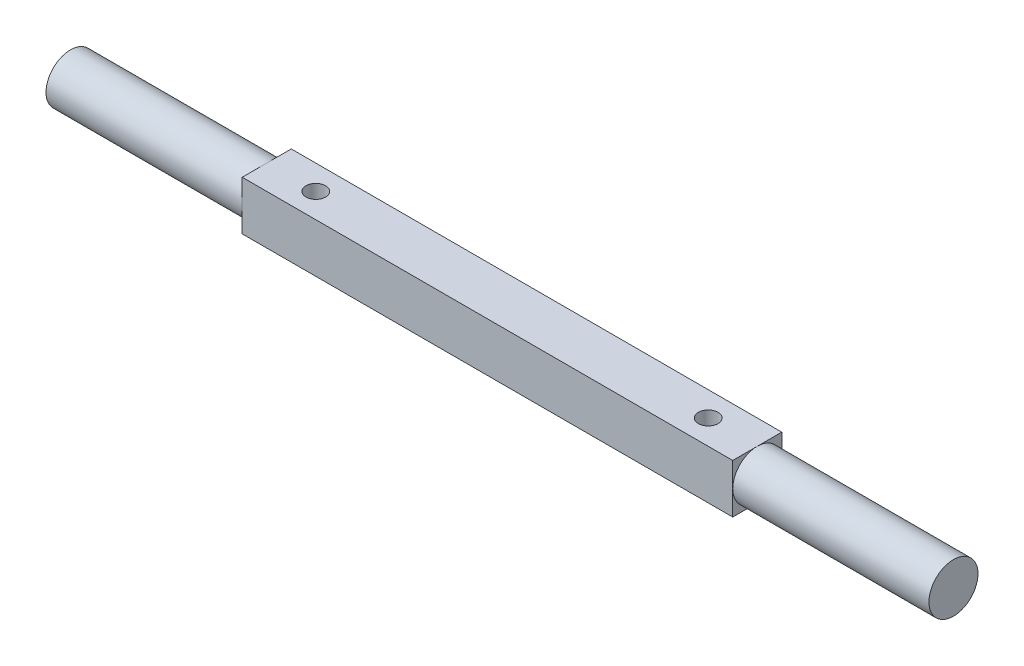
SolidWorks part; units mm, degrees
ref_plane "Front Plane" through (0, 0, 0) normal (0, 0, 1) x (1, 0, 0)
ref_plane "Top Plane" through (0, 0, 0) normal (0, 1, 0) x (1, 0, 0)
ref_plane "Right Plane" through (0, 0, 0) normal (1, 0, 0) x (0, 0, -1)
sketch "Sketch1" plane through (0, 0, 0) normal (0, 1, 0) x (1, 0, 0)
  line L1 (-250, 25) -> (250, 25)
  line L2 (-250, 25) -> (-250, -25)
  line L3 (-250, -25) -> (250, -25)
  line L4 (250, 25) -> (250, -25)
  line L5 (-250, 25) -> (250, -25) construction
  line L6 (-250, -25) -> (250, 25) construction
  point P0 (0, 0)
  dimension "D1" = 500
  dimension "D2" = 50
extrude "Boss-Extrude1" add sketch "Sketch1" along normal mid plane 50
sketch "Sketch2" plane through (0, 25, 0) normal (0, 1, 0) x (1, 0, 0)
  line L0 (-250, 0) -> (250, 0) construction
  line L1 (-250, 25) -> (-250, -25) construction
  line L2 (250, -25) -> (250, 25) construction
  line L3 (0, 25) -> (0, -25) construction
  line L4 (250, 25) -> (-250, 25) construction
  line L5 (-250, -25) -> (250, -25) construction
  circle A0 centre (200, 0) radius 10
  circle A1 centre (-200, 0) radius 10
  dimension "D1" = 20
  dimension "D2" = 50
extrude "Cut-Extrude1" cut sketch "Sketch2" against normal through all
sketch "Sketch4" plane through (250, 0, 0) normal (1, 0, 0) x (0, 0, -1)
  circle A0 centre (0, 0) radius 25
  dimension "D1" = 50
extrude "Boss-Extrude2" add sketch "Sketch4" along normal blind 200
sketch "Sketch5" plane through (-250, 0, 0) normal (-1, 0, 0) x (0, 0, 1)
  circle A0 centre (0, 0) radius 25
  dimension "D1" = 50
extrude "Boss-Extrude3" add sketch "Sketch5" along normal blind 200
